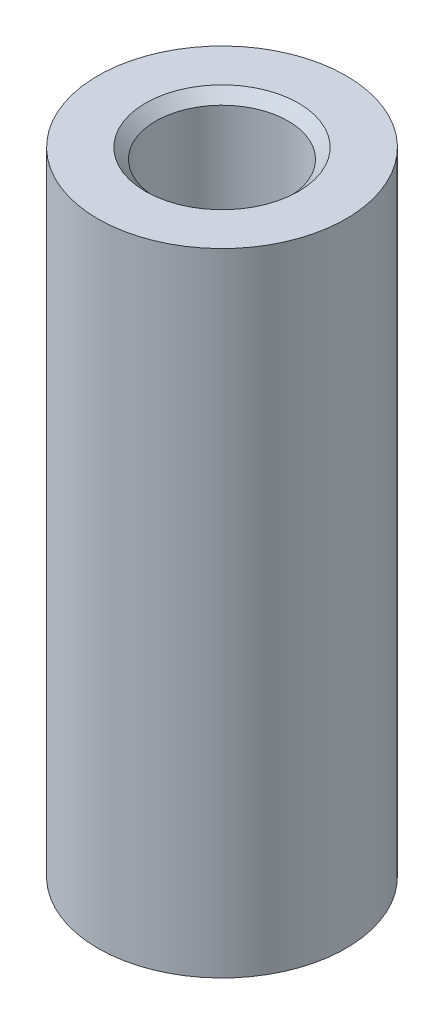
SolidWorks part; units mm, degrees
material "6061-T6 (SS)"
ref_plane "Front Plane" through (0, 0, 0) normal (0, 0, 1) x (1, 0, 0)
ref_plane "Top Plane" through (0, 0, 0) normal (0, 1, 0) x (1, 0, 0)
ref_plane "Right Plane" through (0, 0, 0) normal (1, 0, 0) x (0, 0, -1)
sketch "Sketch1" plane through (0, 0, 0) normal (0, 1, 0) x (1, 0, 0)
  circle A0 centre (0, 0) radius 3
  dimension "D1" = 6
extrude "Boss-Extrude1" add sketch "Sketch1" along normal blind 15.275
hole_wizard "M3 Clearance Hole1" positions "Sketch2" profile "Sketch4" hole size "M3" standard "ANSI Metric" end condition through all
sketch "Sketch2" plane through (0, 15.275, 0) normal (0, 1, 0) x (1, 0, 0)
  point P0 (0, 0)
sketch "Sketch4" plane through (0, 15.275, 0) normal (1, 0, 0) x (0, 0, 1)
  line L0 (0, 0) -> (0, 15.275)
  line L1 (0, 15.275) -> (1.6, 15.275)
  line L2 (1.6, 15.275) -> (1.6, 0)
  line L5 (1.6, 0) -> (0, 0)
  line L11 (0, -6.35) -> (0, 107.95) construction
  dimension "Thru Hole Dia." = 3.2
  dimension "Thru Hole Depth" = 15.275
chamfer "Chamfer1" distance 0.25 angle 45 2 edges at (0, 15.275, 1.6) (0, 0, 1.6)
